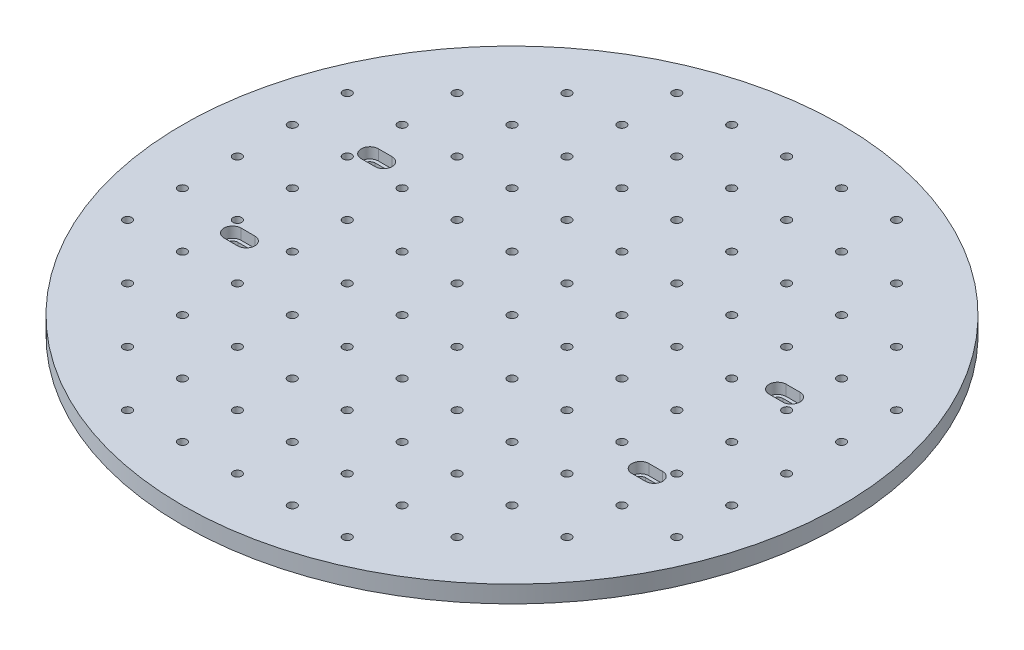
SolidWorks part; units mm, degrees
ref_plane "Front Plane" through (0, 0, 0) normal (0, 0, 1) x (1, 0, 0)
ref_plane "Top Plane" through (0, 0, 0) normal (0, 1, 0) x (1, 0, 0)
ref_plane "Right Plane" through (0, 0, 0) normal (1, 0, 0) x (0, 0, -1)
sketch "Sketch1" plane through (0, 0, 0) normal (0, 1, 0) x (1, 0, 0)
  circle A0 centre (0, 0) radius 304.8
  dimension "D1" = 609.6
extrude "Extrude1" add sketch "Sketch1" along normal blind 15.875
sketch "Sketch2" plane through (0, 15.875, 0) normal (0, 1, 0) x (1, 0, 0)
  line L0 (0, 0) -> (77.8944, 0) construction
  line L1 (0, 0) -> (0, 71.3719) construction
  circle A1 centre (-203.2, -254) radius 3.9688 [skipped]
  circle A2 centre (-152.4, -254) radius 3.9688 [skipped]
  circle A3 centre (-101.6, -254) radius 3.9688
  circle A4 centre (-50.8, -254) radius 3.9688
  circle A5 centre (0, -254) radius 3.9688
  circle A6 centre (50.8, -254) radius 3.9688
  circle A7 centre (101.6, -254) radius 3.9688
  circle A8 centre (152.4, -254) radius 3.9688 [skipped]
  circle A9 centre (203.2, -254) radius 3.9688 [skipped]
  circle A10 centre (254, -254) radius 3.9688 [skipped]
  circle A11 centre (-254, -203.2) radius 3.9688 [skipped]
  circle A12 centre (-203.2, -203.2) radius 3.9688 [skipped]
  circle A13 centre (-152.4, -203.2) radius 3.9688
  circle A14 centre (-101.6, -203.2) radius 3.9688
  circle A15 centre (-50.8, -203.2) radius 3.9688
  circle A16 centre (0, -203.2) radius 3.9688
  circle A17 centre (50.8, -203.2) radius 3.9688
  circle A18 centre (101.6, -203.2) radius 3.9688
  circle A19 centre (152.4, -203.2) radius 3.9688
  circle A20 centre (203.2, -203.2) radius 3.9688 [skipped]
  circle A21 centre (254, -203.2) radius 3.9688 [skipped]
  circle A22 centre (-254, -152.4) radius 3.9688 [skipped]
  circle A23 centre (-203.2, -152.4) radius 3.9688
  circle A24 centre (-152.4, -152.4) radius 3.9688
  circle A25 centre (-101.6, -152.4) radius 3.9688
  circle A26 centre (-50.8, -152.4) radius 3.9688
  circle A27 centre (0, -152.4) radius 3.9688
  circle A28 centre (50.8, -152.4) radius 3.9688
  circle A29 centre (101.6, -152.4) radius 3.9688
  circle A30 centre (152.4, -152.4) radius 3.9688
  circle A31 centre (203.2, -152.4) radius 3.9688
  circle A32 centre (254, -152.4) radius 3.9688 [skipped]
  circle A33 centre (-254, -101.6) radius 3.9688
  circle A34 centre (-203.2, -101.6) radius 3.9688
  circle A35 centre (-152.4, -101.6) radius 3.9688
  circle A36 centre (-101.6, -101.6) radius 3.9688
  circle A37 centre (-50.8, -101.6) radius 3.9688
  circle A38 centre (0, -101.6) radius 3.9688
  circle A39 centre (50.8, -101.6) radius 3.9688
  circle A40 centre (101.6, -101.6) radius 3.9688
  circle A41 centre (152.4, -101.6) radius 3.9688
  circle A42 centre (203.2, -101.6) radius 3.9688
  circle A43 centre (254, -101.6) radius 3.9688
  circle A44 centre (-254, -50.8) radius 3.9688
  circle A45 centre (-203.2, -50.8) radius 3.9688
  circle A46 centre (-152.4, -50.8) radius 3.9688
  circle A47 centre (-101.6, -50.8) radius 3.9688
  circle A48 centre (-50.8, -50.8) radius 3.9688
  circle A49 centre (0, -50.8) radius 3.9688
  circle A50 centre (50.8, -50.8) radius 3.9688
  circle A51 centre (101.6, -50.8) radius 3.9688
  circle A52 centre (152.4, -50.8) radius 3.9688
  circle A53 centre (203.2, -50.8) radius 3.9688
  circle A54 centre (254, -50.8) radius 3.9688
  circle A55 centre (-254, 0) radius 3.9688
  circle A56 centre (-203.2, 0) radius 3.9688
  circle A57 centre (-152.4, 0) radius 3.9688
  circle A58 centre (-101.6, 0) radius 3.9688
  circle A59 centre (-50.8, 0) radius 3.9688
  circle A60 centre (0, 0) radius 3.9688
  circle A61 centre (50.8, 0) radius 3.9688
  circle A62 centre (101.6, 0) radius 3.9688
  circle A63 centre (152.4, 0) radius 3.9688
  circle A64 centre (203.2, 0) radius 3.9688
  circle A65 centre (254, 0) radius 3.9688
  circle A66 centre (-254, 50.8) radius 3.9688
  circle A67 centre (-203.2, 50.8) radius 3.9688
  circle A68 centre (-152.4, 50.8) radius 3.9688
  circle A69 centre (-101.6, 50.8) radius 3.9688
  circle A70 centre (-50.8, 50.8) radius 3.9688
  circle A71 centre (0, 50.8) radius 3.9688
  circle A72 centre (50.8, 50.8) radius 3.9688
  circle A73 centre (101.6, 50.8) radius 3.9688
  circle A74 centre (152.4, 50.8) radius 3.9688
  circle A75 centre (203.2, 50.8) radius 3.9688
  circle A76 centre (254, 50.8) radius 3.9688
  circle A77 centre (-254, 101.6) radius 3.9688
  circle A78 centre (-203.2, 101.6) radius 3.9688
  circle A79 centre (-152.4, 101.6) radius 3.9688
  circle A80 centre (-101.6, 101.6) radius 3.9688
  circle A81 centre (-50.8, 101.6) radius 3.9688
  circle A82 centre (0, 101.6) radius 3.9688
  circle A83 centre (50.8, 101.6) radius 3.9688
  circle A84 centre (101.6, 101.6) radius 3.9688
  circle A85 centre (152.4, 101.6) radius 3.9688
  circle A86 centre (203.2, 101.6) radius 3.9688
  circle A87 centre (254, 101.6) radius 3.9688
  circle A88 centre (-254, 152.4) radius 3.9688 [skipped]
  circle A89 centre (-203.2, 152.4) radius 3.9688
  circle A90 centre (-152.4, 152.4) radius 3.9688
  circle A91 centre (-101.6, 152.4) radius 3.9688
  circle A92 centre (-50.8, 152.4) radius 3.9688
  circle A93 centre (0, 152.4) radius 3.9688
  circle A94 centre (50.8, 152.4) radius 3.9688
  circle A95 centre (101.6, 152.4) radius 3.9688
  circle A96 centre (152.4, 152.4) radius 3.9688
  circle A97 centre (203.2, 152.4) radius 3.9688
  circle A98 centre (254, 152.4) radius 3.9688 [skipped]
  circle A99 centre (-254, 203.2) radius 3.9688 [skipped]
  circle A100 centre (-203.2, 203.2) radius 3.9688 [skipped]
  circle A101 centre (-152.4, 203.2) radius 3.9688
  circle A102 centre (-101.6, 203.2) radius 3.9688
  circle A103 centre (-50.8, 203.2) radius 3.9688
  circle A104 centre (0, 203.2) radius 3.9688
  circle A105 centre (50.8, 203.2) radius 3.9688
  circle A106 centre (101.6, 203.2) radius 3.9688
  circle A107 centre (152.4, 203.2) radius 3.9688
  circle A108 centre (203.2, 203.2) radius 3.9688 [skipped]
  circle A109 centre (254, 203.2) radius 3.9688 [skipped]
  circle A110 centre (-254, 254) radius 3.9688 [skipped]
  circle A111 centre (-203.2, 254) radius 3.9688 [skipped]
  circle A112 centre (-152.4, 254) radius 3.9688 [skipped]
  circle A113 centre (-101.6, 254) radius 3.9688
  circle A114 centre (-50.8, 254) radius 3.9688
  circle A115 centre (0, 254) radius 3.9688
  circle A116 centre (50.8, 254) radius 3.9688
  circle A117 centre (101.6, 254) radius 3.9688
  circle A118 centre (152.4, 254) radius 3.9688 [skipped]
  circle A119 centre (203.2, 254) radius 3.9688 [skipped]
  circle A120 centre (254, 254) radius 3.9688 [skipped]
  circle A121 centre (-254, -254) radius 3.9688 [skipped]
extrude "Extrude2" cut sketch "Sketch2" against normal through all
sketch "Sketch3" plane through (0, 15.875, 0) normal (0, 1, 0) x (1, 0, 0)
  line L0 (182.1942, 68.4022) -> (194.8942, 68.4022)
  line L1 (-194.9958, 68.4022) -> (-182.2958, 68.4022)
  line L2 (182.1942, 58.5978) -> (194.8942, 58.5978)
  line L3 (-194.9958, 58.5978) -> (-182.2958, 58.5978)
  line L4 (-194.9958, -58.5978) -> (-182.2958, -58.5978)
  line L5 (-194.9958, -68.4022) -> (-182.2958, -68.4022)
  line L6 (182.1942, -58.5978) -> (194.8942, -58.5978)
  line L7 (182.1942, -68.4022) -> (194.8942, -68.4022)
  arc A0 (-194.9958, 68.4022) -> (-194.9958, 58.5978) centre (-194.9958, 63.5) ccw
  arc A1 (-182.2958, 58.5978) -> (-182.2958, 68.4022) centre (-182.2958, 63.5) ccw
  circle A2 centre (0, 0) radius 3.9688 construction
  arc A3 (194.8942, 58.5978) -> (194.8942, 68.4022) centre (194.8942, 63.5) ccw
  arc A4 (182.1942, 68.4022) -> (182.1942, 58.5978) centre (182.1942, 63.5) ccw
  arc A5 (-182.2958, -68.4022) -> (-182.2958, -58.5978) centre (-182.2958, -63.5) ccw
  arc A6 (-194.9958, -58.5978) -> (-194.9958, -68.4022) centre (-194.9958, -63.5) ccw
  arc A7 (194.8942, -68.4022) -> (194.8942, -58.5978) centre (194.8942, -63.5) ccw
  arc A8 (182.1942, -58.5978) -> (182.1942, -68.4022) centre (182.1942, -63.5) ccw
  dimension "D1" = 9.8044
  dimension "D2" = 63.5
  dimension "D3" = 182.2958
extrude "Extrude3" cut sketch "Sketch3" against normal blind 15.875
sketch "Sketch4" plane through (0, 15.875, 0) normal (0, 1, 0) x (1, 0, 0)
  line L0 (-182.2958, -55.5625) -> (-194.9958, -55.5625)
  line L1 (-182.2958, 71.4375) -> (-194.9958, 71.4375)
  line L2 (-194.9958, 55.5625) -> (-182.2958, 55.5625)
  line L3 (-182.2958, 68.4022) -> (-194.9958, 68.4022)
  line L4 (-194.9958, 58.5978) -> (-182.2958, 58.5978)
  line L5 (-182.2958, 68.4022) -> (-194.9958, 68.4022)
  line L6 (-194.9958, 58.5978) -> (-182.2958, 58.5978)
  line L7 (-194.9958, -71.4375) -> (-182.2958, -71.4375)
  line L8 (182.1942, 58.5978) -> (194.8942, 58.5978) construction
  line L9 (194.8942, 68.4022) -> (182.1942, 68.4022) construction
  line L10 (-182.2958, -58.5978) -> (-194.9958, -58.5978)
  line L11 (-194.9958, -68.4022) -> (-182.2958, -68.4022)
  line L12 (-182.2958, -58.5978) -> (-194.9958, -58.5978)
  line L13 (-194.9958, -68.4022) -> (-182.2958, -68.4022)
  line L14 (182.1942, 58.5978) -> (194.8942, 58.5978)
  line L15 (194.8942, 68.4022) -> (182.1942, 68.4022)
  line L16 (182.1942, -68.4022) -> (194.8942, -68.4022) construction
  line L17 (194.8942, -58.5978) -> (182.1942, -58.5978) construction
  line L18 (182.1942, -68.4022) -> (194.8942, -68.4022)
  line L19 (194.8942, -58.5978) -> (182.1942, -58.5978)
  line L20 (182.1942, -71.4375) -> (194.8942, -71.4375)
  line L21 (194.8942, -55.5625) -> (182.1942, -55.5625)
  line L22 (182.1942, 55.5625) -> (194.8942, 55.5625)
  line L23 (194.8942, 71.4375) -> (182.1942, 71.4375)
  arc A0 (-194.9958, 71.4375) -> (-194.9958, 55.5625) centre (-194.9958, 63.5) ccw
  arc A1 (-182.2958, 55.5625) -> (-182.2958, 71.4375) centre (-182.2958, 63.5) ccw
  arc A2 (-194.9958, 68.4022) -> (-194.9958, 58.5978) centre (-194.9958, 63.5) ccw
  arc A3 (-182.2958, 58.5978) -> (-182.2958, 68.4022) centre (-182.2958, 63.5) ccw
  arc A4 (-194.9958, 68.4022) -> (-194.9958, 58.5978) centre (-194.9958, 63.5) ccw
  arc A5 (-182.2958, 58.5978) -> (-182.2958, 68.4022) centre (-182.2958, 63.5) ccw
  arc A6 (182.1942, 68.4022) -> (182.1942, 58.5978) centre (182.1942, 63.5) ccw construction
  arc A7 (194.8942, 58.5978) -> (194.8942, 68.4022) centre (194.8942, 63.5) ccw construction
  arc A8 (-194.9958, -58.5978) -> (-194.9958, -68.4022) centre (-194.9958, -63.5) ccw
  arc A9 (-182.2958, -68.4022) -> (-182.2958, -58.5978) centre (-182.2958, -63.5) ccw
  arc A10 (-194.9958, -58.5978) -> (-194.9958, -68.4022) centre (-194.9958, -63.5) ccw
  arc A11 (-182.2958, -68.4022) -> (-182.2958, -58.5978) centre (-182.2958, -63.5) ccw
  arc A12 (182.1942, 68.4022) -> (182.1942, 58.5978) centre (182.1942, 63.5) ccw
  arc A13 (194.8942, 58.5978) -> (194.8942, 68.4022) centre (194.8942, 63.5) ccw
  arc A14 (182.1942, -58.5978) -> (182.1942, -68.4022) centre (182.1942, -63.5) ccw construction
  arc A15 (194.8942, -68.4022) -> (194.8942, -58.5978) centre (194.8942, -63.5) ccw construction
  arc A16 (182.1942, -58.5978) -> (182.1942, -68.4022) centre (182.1942, -63.5) ccw
  arc A17 (194.8942, -68.4022) -> (194.8942, -58.5978) centre (194.8942, -63.5) ccw
  arc A18 (-194.9958, -55.5625) -> (-194.9958, -71.4375) centre (-194.9958, -63.5) ccw
  arc A19 (-182.2958, -71.4375) -> (-182.2958, -55.5625) centre (-182.2958, -63.5) ccw
  arc A20 (194.8942, -71.4375) -> (194.8942, -55.5625) centre (194.8942, -63.5) ccw
  arc A21 (182.1942, -55.5625) -> (182.1942, -71.4375) centre (182.1942, -63.5) ccw
  arc A22 (194.8942, 55.5625) -> (194.8942, 71.4375) centre (194.8942, 63.5) ccw
  arc A23 (182.1942, 71.4375) -> (182.1942, 55.5625) centre (182.1942, 63.5) ccw
  dimension "D1" = 0
  dimension "D2" = 3.0353
  dimension "D3" = 0
  dimension "D4" = 3.0353
extrude "Extrude4" cut sketch "Sketch4" against normal blind 9.8298
